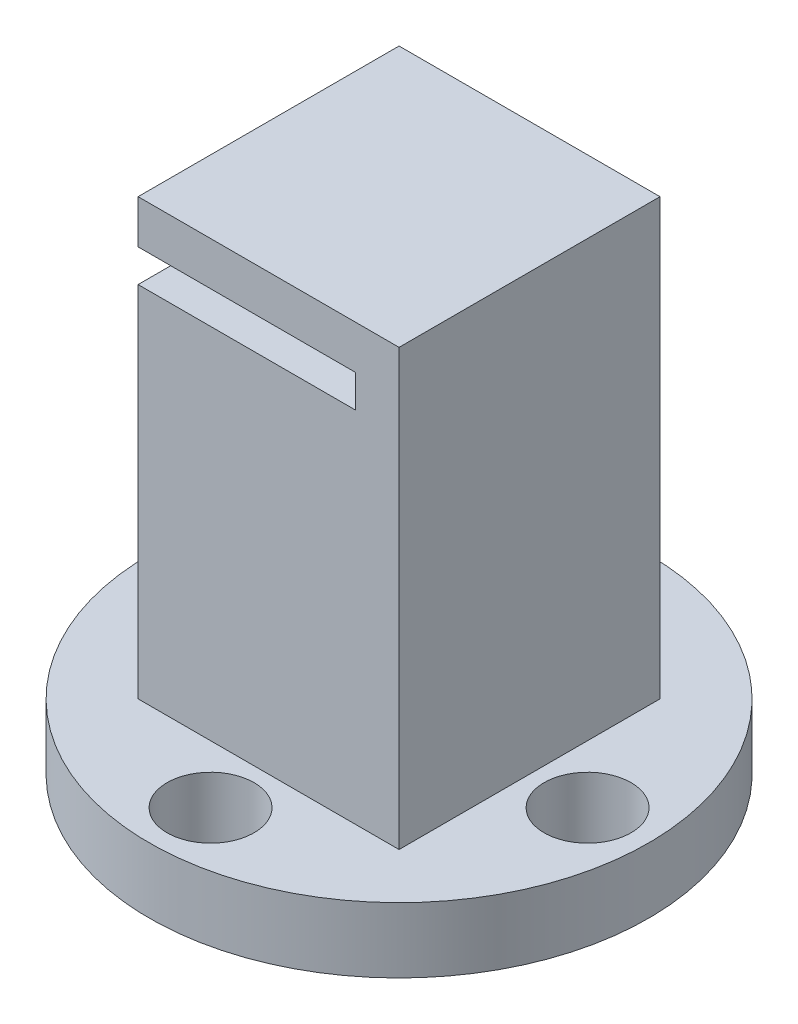
SolidWorks part; units mm, degrees
ref_plane "Alzado" through (0, 0, 0) normal (0, 0, 1) x (1, 0, 0)
ref_plane "Planta" through (0, 0, 0) normal (0, 1, 0) x (1, 0, 0)
ref_plane "Vista lateral" through (0, 0, 0) normal (1, 0, 0) x (0, 0, -1)
sketch "Croquis1" plane through (0, 0, 0) normal (0, 1, 0) x (1, 0, 0)
  line L1 (0, 0) -> (12, 0)
  line L2 (0, 0) -> (0, 12)
  line L3 (0, 12) -> (12, 12)
  line L4 (12, 0) -> (12, 12)
  dimension "D1" = 12
  dimension "D2" = 12
extrude "Saliente-Extruir1" add sketch "Croquis1" along normal blind 20
sketch "Croquis2" plane through (0, 0, 0) normal (0, 0, 1) x (1, 0, 0)
  line L0 (0, 20) -> (0, 0) construction
  line L1 (0, 18) -> (10, 18)
  line L2 (0, 18) -> (0, 16.5)
  line L3 (0, 16.5) -> (10, 16.5)
  line L4 (10, 18) -> (10, 16.5)
  line L5 (0, 20) -> (12, 20) construction
  line L6 (12, 20) -> (12, 0) construction
  dimension "D1" = 1.5
  dimension "D2" = 2
  dimension "D3" = 2
extrude "Cortar-Extruir1" cut sketch "Croquis2" against normal blind 10
sketch "Croquis3" plane through (0, 0, 0) normal (0, -1, 0) x (1, 0, 0)
  line L0 (6, 0) -> (6, -13.845) construction
  line L1 (0, 0) -> (12, 0) construction
  line L2 (0, -6) -> (20.1655, -6) construction
  line L3 (0, -12) -> (0, 0) construction
  circle A0 centre (6, -6) radius 11.4782
  circle A1 centre (14.6685, -6) radius 2
  circle A2 centre (6, -14.6685) radius 2
  circle A3 centre (-2.6685, -6) radius 2
  circle A4 centre (6, 2.6685) radius 2
  point P21 (6, -6)
  dimension "D1" = 4
  dimension "D2" = 4
extrude "Saliente-Extruir2" add sketch "Croquis3" along normal blind 3
